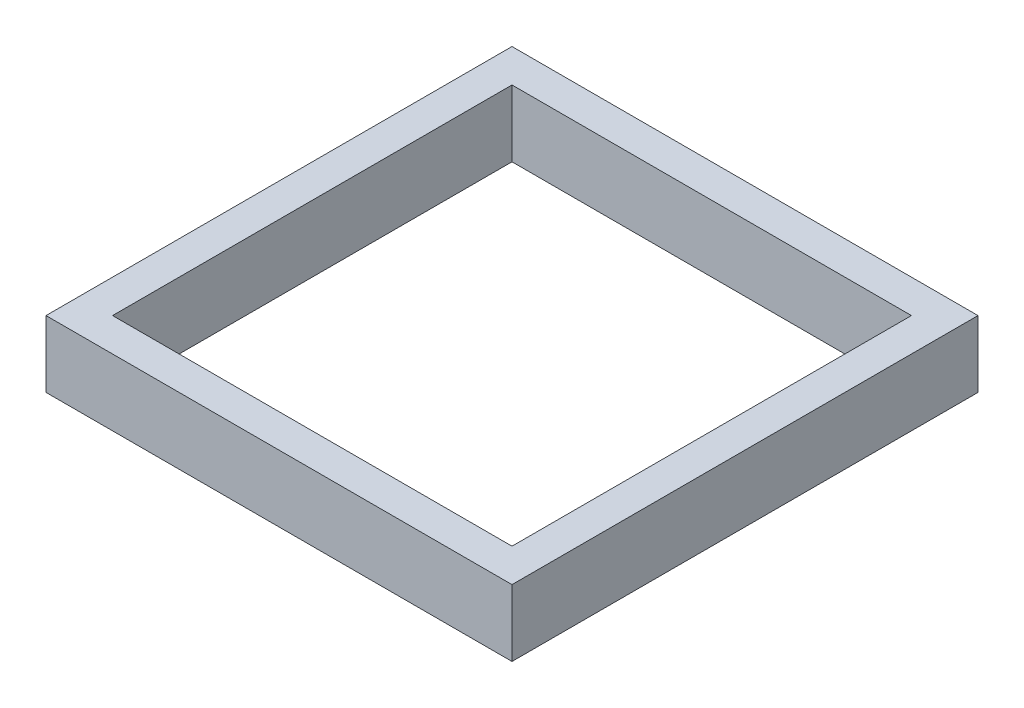
SolidWorks part; units mm, degrees
ref_plane "Front Plane" through (0, 0, 0) normal (0, 0, 1) x (1, 0, 0)
ref_plane "Top Plane" through (0, 0, 0) normal (0, 1, 0) x (1, 0, 0)
ref_plane "Right Plane" through (0, 0, 0) normal (1, 0, 0) x (0, 0, -1)
sketch "Sketch1" plane through (0, 0, 0) normal (0, 1, 0) x (1, 0, 0)
  line L0 (-593.1944, 106.6398) -> (6.8056, 106.6398)
  line L1 (-643.1944, 156.6398) -> (56.8056, 156.6398)
  line L2 (-643.1944, 156.6398) -> (-643.1944, -543.3602)
  line L3 (-643.1944, -543.3602) -> (56.8056, -543.3602)
  line L4 (56.8056, 156.6398) -> (56.8056, -543.3602)
  line L5 (6.8056, 106.6398) -> (6.8056, -493.3602)
  line L6 (-593.1944, -493.3602) -> (6.8056, -493.3602)
  line L7 (-593.1944, 106.6398) -> (-593.1944, -493.3602)
  dimension "D1" = 700
  dimension "D2" = 700
  dimension "D3" = 50
extrude "Boss-Extrude1" add sketch "Sketch1" along normal blind 100
